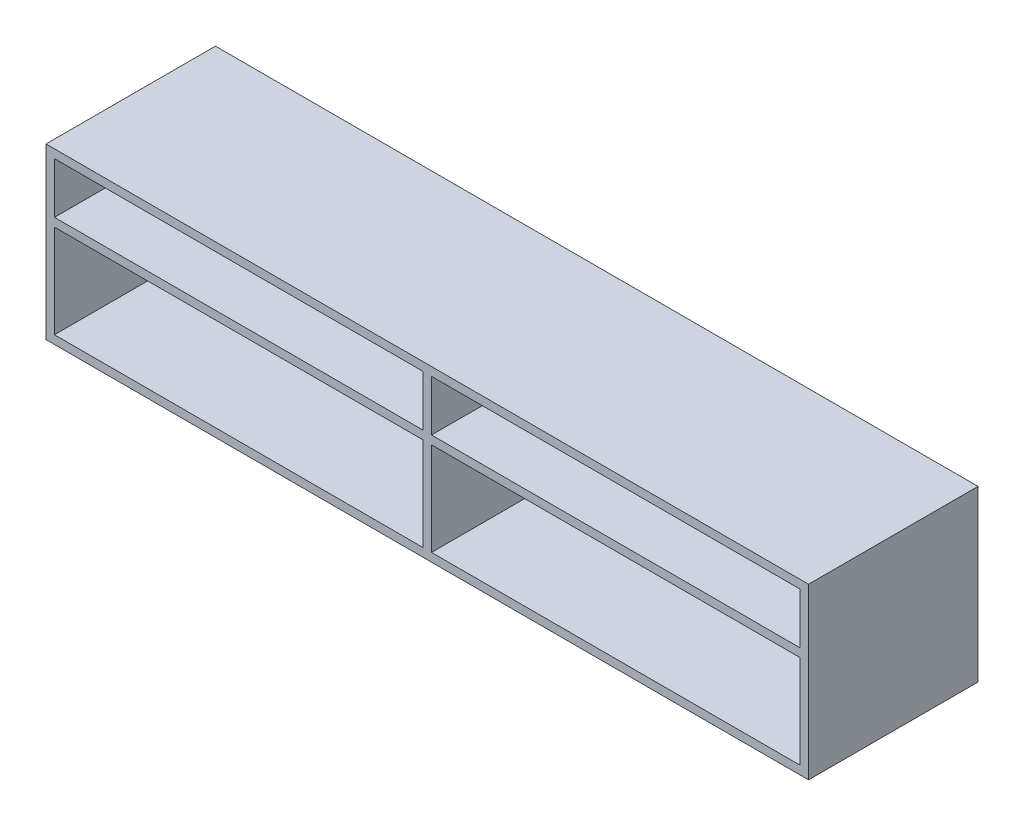
SolidWorks part; units mm, degrees
ref_plane "Front Plane" through (0, 0, 0) normal (0, 0, 1) x (1, 0, 0)
ref_plane "Top Plane" through (0, 0, 0) normal (0, 1, 0) x (1, 0, 0)
ref_plane "Right Plane" through (0, 0, 0) normal (1, 0, 0) x (0, 0, -1)
sketch "Sketch1" plane through (0, 0, 0) normal (0, 0, 1) x (1, 0, 0)
  line L0 (0, 0) -> (1800, 0)
  line L1 (1800, 0) -> (1800, 400)
  line L2 (1800, 400) -> (0, 400)
  line L3 (0, 400) -> (0, 0)
  line L4 (20, 380) -> (20, 260)
  line L5 (20, 20) -> (890, 20)
  line L6 (1780, 20) -> (1780, 240)
  line L7 (1780, 380) -> (910, 380)
  line L8 (20, 240) -> (20, 20)
  line L9 (20, 240) -> (890, 240)
  line L10 (20, 260) -> (890, 260)
  line L11 (1780, 260) -> (1780, 380)
  line L12 (20, 380) -> (20, 20) construction
  line L13 (910, 20) -> (1780, 20)
  line L14 (1780, 20) -> (1780, 380) construction
  line L15 (890, 380) -> (890, 260)
  line L16 (910, 380) -> (910, 260)
  line L17 (890, 380) -> (20, 380)
  line L18 (910, 240) -> (910, 20)
  line L19 (20, 20) -> (1780, 20) construction
  line L20 (890, 240) -> (890, 20)
  line L21 (910, 240) -> (1780, 240)
  line L22 (1780, 380) -> (20, 380) construction
  line L23 (910, 260) -> (1780, 260)
  point P9 (900, 500)
  point P10 (900, 20)
  point P15 (890, 500)
  point P17 (910, 500)
  dimension "D1" = 1800
  dimension "D2" = 400
  dimension "D3" = 20
extrude "Boss-Extrude1" add sketch "Sketch1" along normal blind 400
